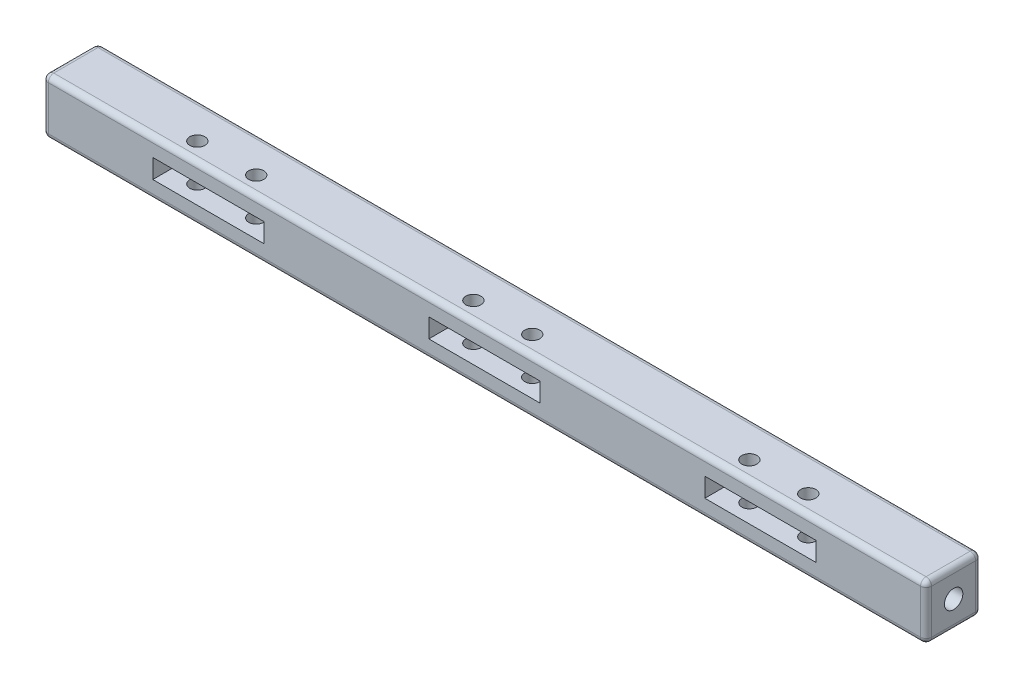
SolidWorks part; units mm, degrees
ref_plane "Plan de face" through (0, 0, 0) normal (0, 0, 1) x (1, 0, 0)
ref_plane "Plan de dessus" through (0, 0, 0) normal (0, 1, 0) x (1, 0, 0)
ref_plane "Plan de droite" through (0, 0, 0) normal (1, 0, 0) x (0, 0, -1)
sketch "Esquisse1" plane through (0, 0, 0) normal (1, 0, 0) x (0, 0, -1)
  line L0 (-5.1072, 0) -> (13.2475, 0) construction
  line L10 (6, 7.5) -> (-6, 7.5)
  line L11 (7.5, 6) -> (7.5, -6)
  line L12 (6, -7.5) -> (-6, -7.5)
  line L13 (-7.5, 6) -> (-7.5, -6)
  line L14 (7.5, 7.5) -> (-7.5, -7.5) construction
  line L15 (7.5, -7.5) -> (-7.5, 7.5) construction
  arc A4 (6, 7.5) -> (7.5, 6) centre (6, 6) cw
  arc A5 (7.5, -6) -> (6, -7.5) centre (6, -6) cw
  arc A6 (-6, -7.5) -> (-7.5, -6) centre (-6, -6) cw
  arc A7 (-6, 7.5) -> (-7.5, 6) centre (-6, 6) ccw
  point P3 (0, 0)
  dimension "D3" = 1.5
  dimension "D1" = 15
  dimension "D2" = 15
extrude "Boss.-Extru.1" add sketch "Esquisse1" along normal blind 120
sketch "Esquisse2" plane through (0, 0, 7.5) normal (0, 0, 1) x (1, 0, 0)
  line L0 (0, 0) -> (313.4757, 0) construction
  line L2 (15.1, 2.6) -> (-15.1, 2.6)
  line L3 (15.1, 2.6) -> (15.1, -2.6)
  line L4 (15.1, -2.6) -> (-15.1, -2.6)
  line L5 (-15.1, 2.6) -> (-15.1, -2.6)
  line L6 (15.1, 2.6) -> (-15.1, -2.6) construction
  line L7 (15.1, -2.6) -> (-15.1, 2.6) construction
  line L8 (90.1, -2.6) -> (59.9, -2.6)
  line L10 (90.1, -2.6) -> (90.1, 2.6)
  line L11 (90.1, 2.6) -> (59.9, 2.6)
  line L12 (59.9, -2.6) -> (59.9, 2.6)
  line L13 (90.1, -2.6) -> (59.9, 2.6) construction
  line L14 (90.1, 2.6) -> (59.9, -2.6) construction
  point P3 (0, 0)
  point P11 (75, 0)
  dimension "D1" = 30.2
  dimension "D2" = 5.2
  dimension "D3" = 75
extrude "Enlèv. mat.-Extru.1" cut sketch "Esquisse2" against normal blind 10
sketch "Esquisse3" plane through (0, -2.6, 0) normal (0, 1, 0) x (1, 0, 0)
  line L0 (0, -2.5) -> (15.1, -2.5) construction
  line L1 (0, 2.5) -> (0, -7.5) construction
  line L3 (59.9, -2.5) -> (165.1, -2.5) construction
  line L4 (0, -7.5) -> (15.1, -7.5)
  line L5 (15.1, -7.5) -> (15.1, 2.5)
  line L6 (15.1, 2.5) -> (0, 2.5)
  line L7 (0, 2.5) -> (0, -7.5)
  line L8 (0, -7.5) -> (15.1, -7.5)
  line L9 (15.1, -7.5) -> (15.1, 2.5)
  line L10 (15.1, 2.5) -> (0, 2.5)
  line L12 (75, 2.5) -> (75, -7.5) construction
  line L15 (0, 2.5) -> (0, -7.5)
  line L16 (59.9, -7.5) -> (90.1, -7.5)
  line L17 (90.1, -7.5) -> (90.1, 2.5)
  line L18 (90.1, 2.5) -> (59.9, 2.5)
  line L19 (59.9, 2.5) -> (59.9, -7.5)
  line L20 (59.9, -7.5) -> (90.1, -7.5)
  line L22 (90.1, 2.5) -> (59.9, 2.5)
  line L23 (59.9, 2.5) -> (59.9, -7.5)
  line L26 (90.1, -7.5) -> (90.1, 2.5)
  circle A0 centre (8, -2.5) radius 2.05
  circle A4 centre (67, -2.5) radius 2.05
  circle A5 centre (83, -2.5) radius 2.05
  dimension "D2" = 4.1
  dimension "D4" = 0
  dimension "D5" = 4.1
  dimension "D3" = 8
  dimension "D6" = 8
  dimension "D1" = 0
extrude "Enlèv. mat.-Extru.2" cut sketch "Esquisse3" against normal through all both and the other way through all
fillet "Congé2" radius 1.5 8 edges at (120, 7.0607, -7.0607) (120, 0, -7.5) (120, -7.0607, -7.0607) (120, -7.5, 0) (120, -7.0607, 7.0607) (120, 0, 7.5) (120, 7.0607, 7.0607) (120, 7.5, 0)
sketch "Esquisse4" plane through (120, 0, 0) normal (1, 0, 0) x (0, 0, -1)
  circle A0 centre (0, 0) radius 2.5
  dimension "D1" = 5
extrude "Enlèv. mat.-Extru.3" cut sketch "Esquisse4" against normal blind 5
mirror "Symétrie6" about plane through (0, 6, -6) normal (-1, 0, 0) of "Boss.-Extru.1", "Enlèv. mat.-Extru.1", "Enlèv. mat.-Extru.2", "Congé2", "Enlèv. mat.-Extru.3"
sketch "Esquisse5" plane through (0, 7.5, 0) normal (0, 1, 0) x (1, 0, 0)
  line L0 (118.5, 0) -> (71.3138, 0) construction
  line L1 (118.5, -6) -> (118.5, 6) construction
